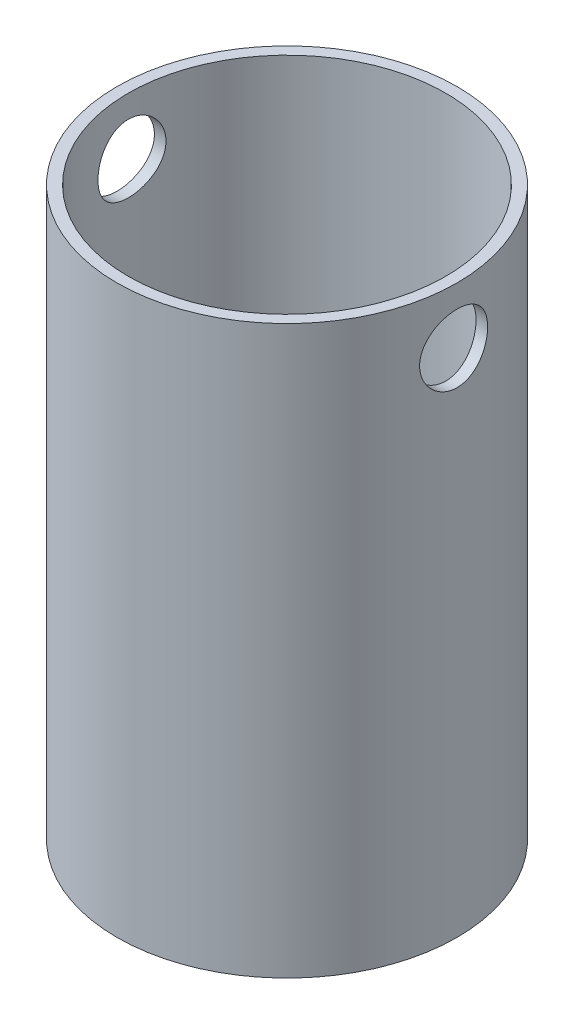
SolidWorks part; units mm, degrees
material "6063-T6"
ref_plane "Front Plane" through (0, 0, 0) normal (0, 0, 1) x (1, 0, 0)
ref_plane "Top Plane" through (0, 0, 0) normal (0, 1, 0) x (1, 0, 0)
ref_plane "Right Plane" through (0, 0, 0) normal (1, 0, 0) x (0, 0, -1)
sketch "Sketch1" plane through (0, 0, 0) normal (0, 1, 0) x (1, 0, 0)
  circle A0 centre (0, 0) radius 14
  circle A1 centre (0, 0) radius 15
  dimension "D1" = 30
  dimension "D2" = 28
extrude "Boss-Extrude1" add sketch "Sketch1" along normal blind 50
sketch "Sketch2" plane through (0, 0, 0) normal (1, 0, 0) x (0, 0, -1)
  line L0 (14, 50) -> (-14, 50) construction
  circle A0 centre (0, 45) radius 3
  dimension "D1" = 5
extrude "Cut-Extrude1" cut sketch "Sketch2" against normal mid plane 30
